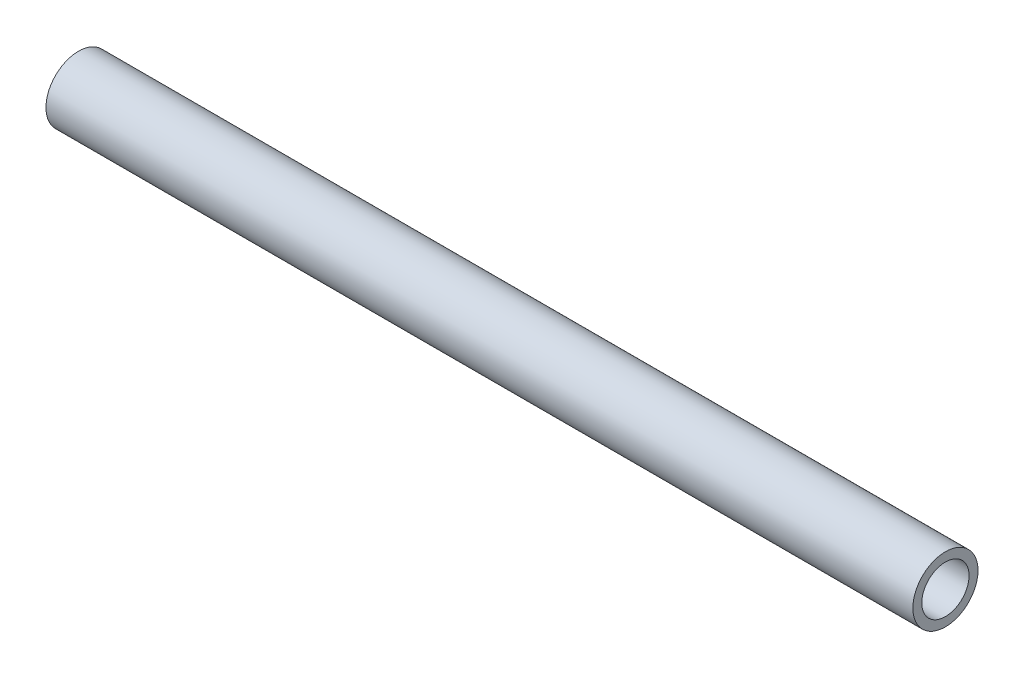
SolidWorks part; units mm, degrees
ref_plane "Front Plane" through (0, 0, 0) normal (0, 0, 1) x (1, 0, 0)
ref_plane "Top Plane" through (0, 0, 0) normal (0, 1, 0) x (1, 0, 0)
ref_plane "Right Plane" through (0, 0, 0) normal (1, 0, 0) x (0, 0, -1)
sketch "Sketch1" plane through (0, 0, 0) normal (1, 0, 0) x (0, 0, -1)
  circle A0 centre (0, 0) radius 13.15
  circle A1 centre (0, 0) radius 9.55
  dimension "D1" = 26.3
  dimension "D2" = 19.1
extrude "Boss-Extrude1" add sketch "Sketch1" along normal blind 350
